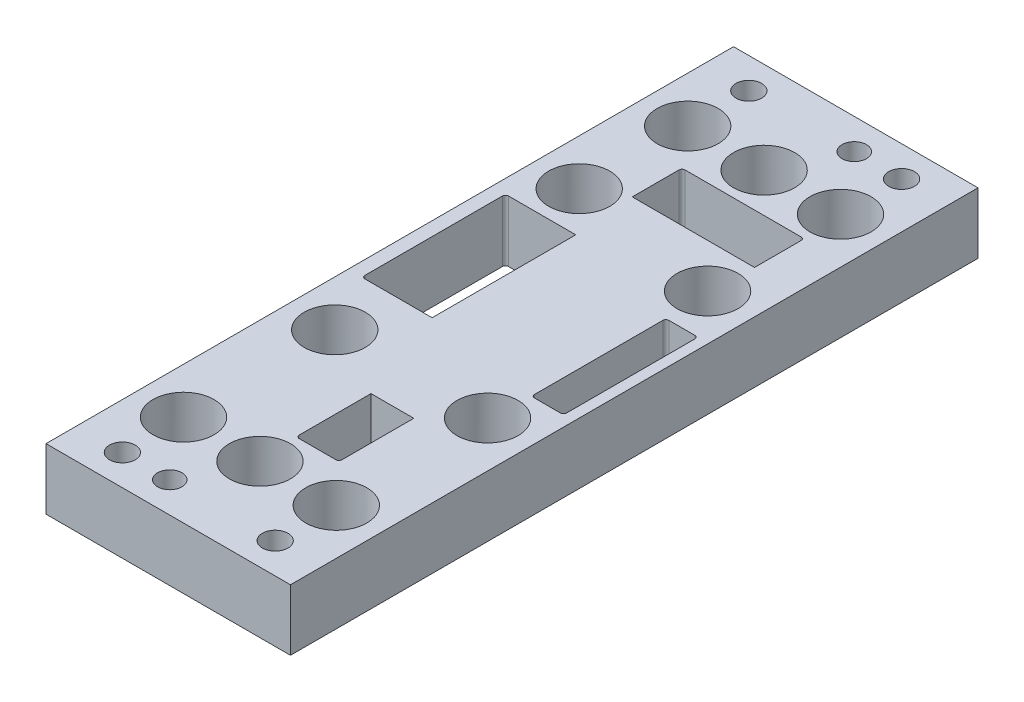
SolidWorks part; units mm, degrees
material "Plain Carbon Steel"
ref_plane "Front Plane" through (0, 0, 0) normal (0, 0, 1) x (1, 0, 0)
ref_plane "Top Plane" through (0, 0, 0) normal (0, 1, 0) x (1, 0, 0)
ref_plane "Right Plane" through (0, 0, 0) normal (1, 0, 0) x (0, 0, -1)
sketch "Sketch1" plane through (0, 0, 0) normal (0, 1, 0) x (1, 0, 0)
  line L0 (-46, 0) -> (34, 0) construction
  line L1 (-46, -112.5) -> (34, -112.5)
  line L2 (-46, -112.5) -> (-46, 112.5)
  line L3 (-46, 112.5) -> (34, 112.5)
  line L4 (34, -112.5) -> (34, 112.5)
  dimension "D1" = 34
  dimension "D2" = 46
  dimension "D3" = 225
extrude "Boss-Extrude1" add sketch "Sketch1" against normal blind 20
sketch "Sketch2" plane through (0, 0, 0) normal (0, 1, 0) x (1, 0, 0)
  line L0 (18, -9.64) -> (29.5, -9.64) construction
  line L1 (29.5, 14.36) -> (18, 14.36) construction
  line L2 (30.5, -8.64) -> (30.5, 13.36) construction
  line L3 (20, -9.64) -> (29.5, -9.64) construction
  line L4 (29.5, 14.36) -> (20, 14.36) construction
  line L5 (30.5, -8.64) -> (30.5, 13.36) construction
  line L6 (20, 14.36) -> (20, -9.64) construction
  line L7 (22, -9.64) -> (22, 14.36) construction
  line L9 (21, -19.64) -> (29.5, -19.64)
  line L10 (20, -18.64) -> (20, 23.36)
  line L11 (21, 24.36) -> (29.5, 24.36)
  line L12 (30.5, -18.64) -> (30.5, 23.36)
  arc A0 (29.5, -9.64) -> (30.5, -8.64) centre (29.5, -8.64) ccw construction
  arc A1 (30.5, 13.36) -> (29.5, 14.36) centre (29.5, 13.36) ccw construction
  arc A2 (29.5, -9.64) -> (30.5, -8.64) centre (29.5, -8.64) ccw construction
  arc A3 (30.5, 13.36) -> (29.5, 14.36) centre (29.5, 13.36) ccw construction
  arc A4 (21, -19.64) -> (20, -18.64) centre (21, -18.64) cw
  arc A5 (29.5, -19.64) -> (30.5, -18.64) centre (29.5, -18.64) ccw
  arc A6 (29.5, 24.36) -> (30.5, 23.36) centre (29.5, 23.36) cw
  arc A7 (20, 23.36) -> (21, 24.36) centre (21, 23.36) cw
  dimension "D6" = 1
  dimension "D1" = 2
  dimension "D2" = 10.5
  dimension "D3" = 24
  dimension "D4" = 10
  dimension "D5" = 10
extrude "Cut-Extrude1" cut sketch "Sketch2" against normal up to next
sketch "Sketch4" plane through (0, 0, 0) normal (0, 1, 0) x (1, 0, 0)
  line L0 (7, -68.64) -> (7, -43.14) construction
  line L2 (-7, -43.14) -> (-7, -68.64) construction
  line L3 (-6, -69.64) -> (6, -69.64) construction
  line L4 (7, -68.64) -> (7, -45.14)
  line L5 (7, -45.14) -> (-7, -45.14)
  line L6 (-7, -45.14) -> (-7, -68.64)
  line L7 (-6, -69.64) -> (6, -69.64)
  line L8 (-7, -47.14) -> (7, -47.14) construction
  arc A2 (-7, -68.64) -> (-6, -69.64) centre (-6, -68.64) ccw construction
  arc A3 (6, -69.64) -> (7, -68.64) centre (6, -68.64) ccw construction
  arc A6 (-7, -68.64) -> (-6, -69.64) centre (-6, -68.64) ccw
  arc A7 (6, -69.64) -> (7, -68.64) centre (6, -68.64) ccw
  dimension "D1" = 2
extrude "Cut-Extrude2" cut sketch "Sketch4" against normal up to next
sketch "Sketch5" plane through (0, 0, 0) normal (0, 1, 0) x (1, 0, 0)
  line L1 (-16.5, 33.36) -> (-40.5, 33.36) construction
  line L2 (-41.5, 32.36) -> (-41.5, -12.64) construction
  line L3 (-40.5, -13.64) -> (-16.5, -13.64) construction
  line L4 (-18.5, -13.64) -> (-18.5, 33.36)
  line L5 (-18.5, 33.36) -> (-40.5, 33.36)
  line L6 (-41.5, 32.36) -> (-41.5, -12.64)
  line L7 (-40.5, -13.64) -> (-18.5, -13.64)
  line L8 (-20.5, 33.36) -> (-20.5, -13.64) construction
  arc A2 (-40.5, 33.36) -> (-41.5, 32.36) centre (-40.5, 32.36) ccw construction
  arc A3 (-41.5, -12.64) -> (-40.5, -13.64) centre (-40.5, -12.64) ccw construction
  arc A6 (-40.5, 33.36) -> (-41.5, 32.36) centre (-40.5, 32.36) ccw
  arc A7 (-41.5, -12.64) -> (-40.5, -13.64) centre (-40.5, -12.64) ccw
  dimension "D1" = 2
extrude "Cut-Extrude3" cut sketch "Sketch5" against normal up to next
sketch "Sketch6" plane through (0, 0, 0) normal (0, 1, 0) x (1, 0, 0)
  line L0 (19, 69.64) -> (-19, 69.64) construction
  line L1 (-20, 68.64) -> (-20, 51.36) construction
  line L3 (20, 51.36) -> (20, 68.64) construction
  line L4 (19, 69.64) -> (-19, 69.64)
  line L5 (-20, 68.64) -> (-20, 53.36)
  line L6 (-20, 53.36) -> (20, 53.36)
  line L7 (20, 53.36) -> (20, 68.64)
  line L8 (-20, 55.36) -> (20, 55.36) construction
  arc A0 (20, 68.64) -> (19, 69.64) centre (19, 68.64) ccw construction
  arc A1 (-19, 69.64) -> (-20, 68.64) centre (-19, 68.64) ccw construction
  arc A4 (20, 68.64) -> (19, 69.64) centre (19, 68.64) ccw
  arc A5 (-19, 69.64) -> (-20, 68.64) centre (-19, 68.64) ccw
  dimension "D1" = 2
extrude "Cut-Extrude4" cut sketch "Sketch6" against normal up to next
hole_wizard "CBORE for M8 Hex Socket Head Cap Screw1" positions "Sketch10" profile "Sketch9" counterbore size "M8" standard "ISO" end condition through all
sketch "Sketch10" plane through (0, -20, 0) normal (0, -1, 0) x (-1, 0, 0)
  line L0 (-34, 112.5) -> (46, 112.5) construction
  line L1 (-34, -112.5) -> (-34, 112.5) construction
  line L2 (46, 112.5) -> (46, -112.5) construction
  line L3 (46, -112.5) -> (-34, -112.5) construction
  point P0 (-19, 102.5)
  point P2 (31, 102.5)
  point P4 (-19, -102.5)
  point P6 (31, -102.5)
  dimension "D1" = 10
  dimension "D2" = 15
  dimension "D3" = 15
  dimension "D4" = 10
sketch "Sketch9" plane through (19, -20, -102.5) normal (1, 0, 0) x (0, 0, -1)
  line L0 (0, 0) -> (0, 20)
  line L1 (0, 20) -> (4.2, 20)
  line L3 (4.2, 20) -> (4.2, 8.6)
  line L4 (4.2, 8.6) -> (7.5, 8.6)
  line L5 (7.5, 8.6) -> (7.5, 0)
  line L7 (7.5, 0) -> (0, 0)
  line L11 (0, -6.35) -> (0, 107.95) construction
  dimension "Thru Hole Dia." = 8.4
  dimension "Thru Hole Depth" = 20
  dimension "C'Bore Dia." = 15
  dimension "C'Bore Depth" = 8.6
hole_wizard "Ø8.0mm Dowel Hole1" positions "Sketch13" profile "Sketch12" hole size "Ø8.0" standard "ISO" end condition through all
sketch "Sketch13" plane through (0, -20, 0) normal (0, -1, 0) x (-1, 0, 0)
  line L0 (-34, 112.5) -> (46, 112.5) construction
  line L1 (46, -112.5) -> (-34, -112.5) construction
  circle A0 centre (-19, 102.5) radius 7.5 construction
  circle A1 centre (31, -102.5) radius 7.5 construction
  point P0 (-3.5, 102.5)
  point P2 (15.5, -102.5)
  dimension "D1" = 8
  dimension "D3" = 8
  dimension "D2" = 10
  dimension "D4" = 10
sketch "Sketch12" plane through (3.5, -20, -102.5) normal (1, 0, 0) x (0, 0, -1)
  line L0 (0, 0) -> (0, 20)
  line L1 (0, 20) -> (4, 20)
  line L2 (4, 20) -> (4, 0)
  line L5 (4, 0) -> (0, 0)
  line L11 (0, -6.35) -> (0, 107.95) construction
  dimension "Thru Hole Dia." = 8
  dimension "Thru Hole Depth" = 20
sketch "Sketch7" plane through (0, 0, 0) normal (0, 1, 0) x (1, 0, 0)
  line L0 (-46, 112.5) -> (-46, -112.5) construction
  line L1 (34, -112.5) -> (34, 112.5) construction
  line L2 (-6, 112.5) -> (-6, -112.5) construction
  line L3 (34, 112.5) -> (-46, 112.5) construction
  line L4 (-46, -112.5) -> (34, -112.5) construction
  line L5 (-46, 0) -> (34, 0) construction
  circle A1 centre (-31, -33) radius 10
  circle A2 centre (-6, 82.5) radius 10
  circle A3 centre (19, -33) radius 10
  circle A4 centre (-31, 47) radius 10
  circle A5 centre (19, 39) radius 10
  circle A7 centre (-31, -82.5) radius 10
  circle A8 centre (-6, -82.5) radius 10
  circle A10 centre (19, -82.5) radius 10
  circle A11 centre (-31, 82.5) radius 10
  circle A14 centre (19, 82.5) radius 10
  dimension "D1" = 15
  dimension "D9" = 20
  dimension "D2" = 15
  dimension "D3" = 30
  dimension "D4" = 30
  dimension "D5" = 47
  dimension "D6" = 39
  dimension "D8" = 33
extrude "Cut-Extrude5" cut sketch "Sketch7" against normal up to next
ref_plane "Center Plane" through (-6, 0, 0) normal (1, 0, 0) x (0, 0, -1)
